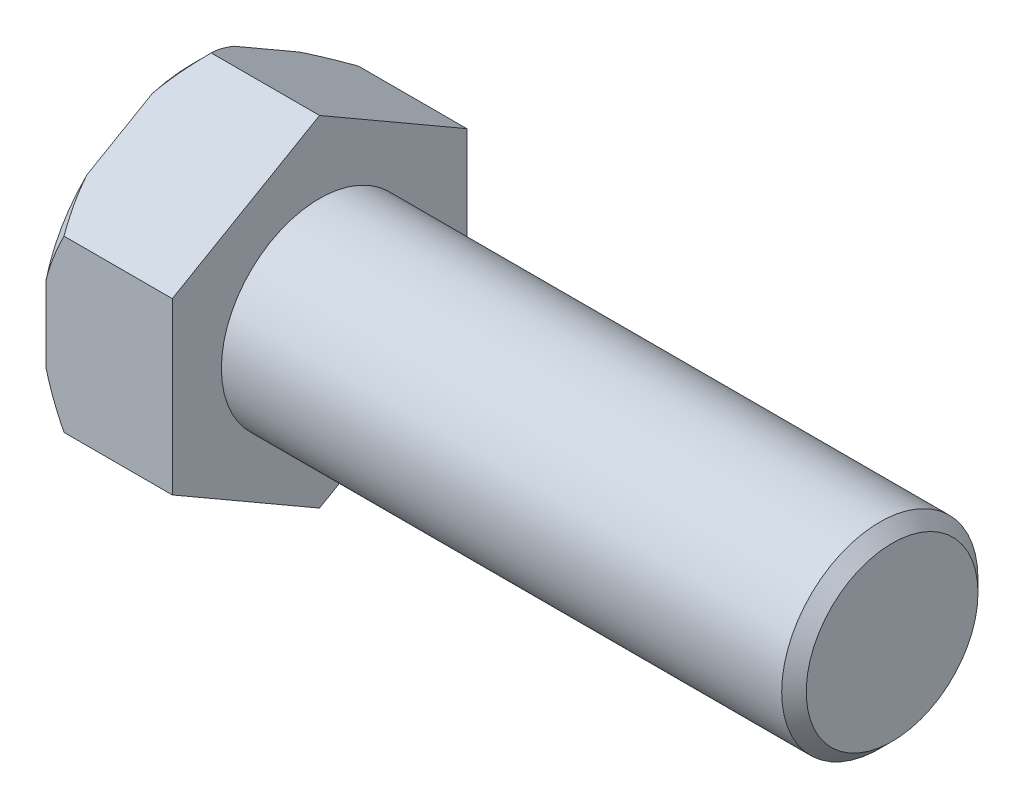
SolidWorks part; units mm, degrees
material "Plain Carbon Steel"
ref_plane "Front Plane" through (0, 0, 0) normal (0, 0, 1) x (1, 0, 0)
ref_plane "Top Plane" through (0, 0, 0) normal (0, 1, 0) x (1, 0, 0)
ref_plane "Right Plane" through (0, 0, 0) normal (1, 0, 0) x (0, 0, -1)
sketch "Sketch1" plane through (0, 0, 0) normal (1, 0, 0) x (0, 0, -1)
  line L1 (0, 20.785) -> (-18.0003, 10.3925)
  line L2 (-18.0003, 10.3925) -> (-18.0003, -10.3925)
  line L3 (-18.0003, -10.3925) -> (0, -20.785)
  line L4 (0, -20.785) -> (18.0003, -10.3925)
  line L5 (18.0003, -10.3925) -> (18.0003, 10.3925)
  line L6 (18.0003, 10.3925) -> (0, 20.785)
  circle A0 centre (0, 0) radius 18.0003 construction
  dimension "E" = 41.57
extrude "Extrude1" add sketch "Sketch1" along normal blind 15.44
sketch "Sketch2" plane through (0, 0, 0) normal (0, 0, 1) x (1, 0, 0)
  line L0 (2.2, 20.785) -> (0, 18.585)
  line L1 (15.44, 20.785) -> (0, 20.785) construction
  line L2 (0, 20.785) -> (0, 10.3925) construction
  line L3 (0, 18.585) -> (0, 20.785)
  line L4 (0, 20.785) -> (2.2, 20.785)
  line L5 (0, 0) -> (4.7427, 0) construction
  dimension "D1" = 45
  dimension "TOPCHM" = 2.2
revolve "Cut-Revolve1" cut sketch "Sketch2" angle 360 about L5
sketch "Sketch3" plane through (15.44, 0, 0) normal (1, 0, 0) x (0, 0, -1)
  circle A0 centre (0, 0) radius 12
  dimension "M" = 24
extrude "Extrude2" add sketch "Sketch3" along normal blind 70
cosmetic thread "Cosmetic Thread1" parameters "B"=54, "D2"=21
chamfer "Chamfer1" distance 1.5 angle 45 1 edges at (85.44, 0, -12)
sketch "Sketch4" plane through (0, 0, 0) normal (-1, 0, 0) x (0, 0, 1)
  line L0 (-17.8674, -5.1146) -> (17.8674, -5.1146) construction
  circle A0 centre (0, 0) radius 18.585 construction
  circle A1 centre (0, 0) radius 18.585 construction
  text T0 "8.8"
extrude "Cut-Extrude1" cut sketch "Sketch4" against normal blind 0.01
